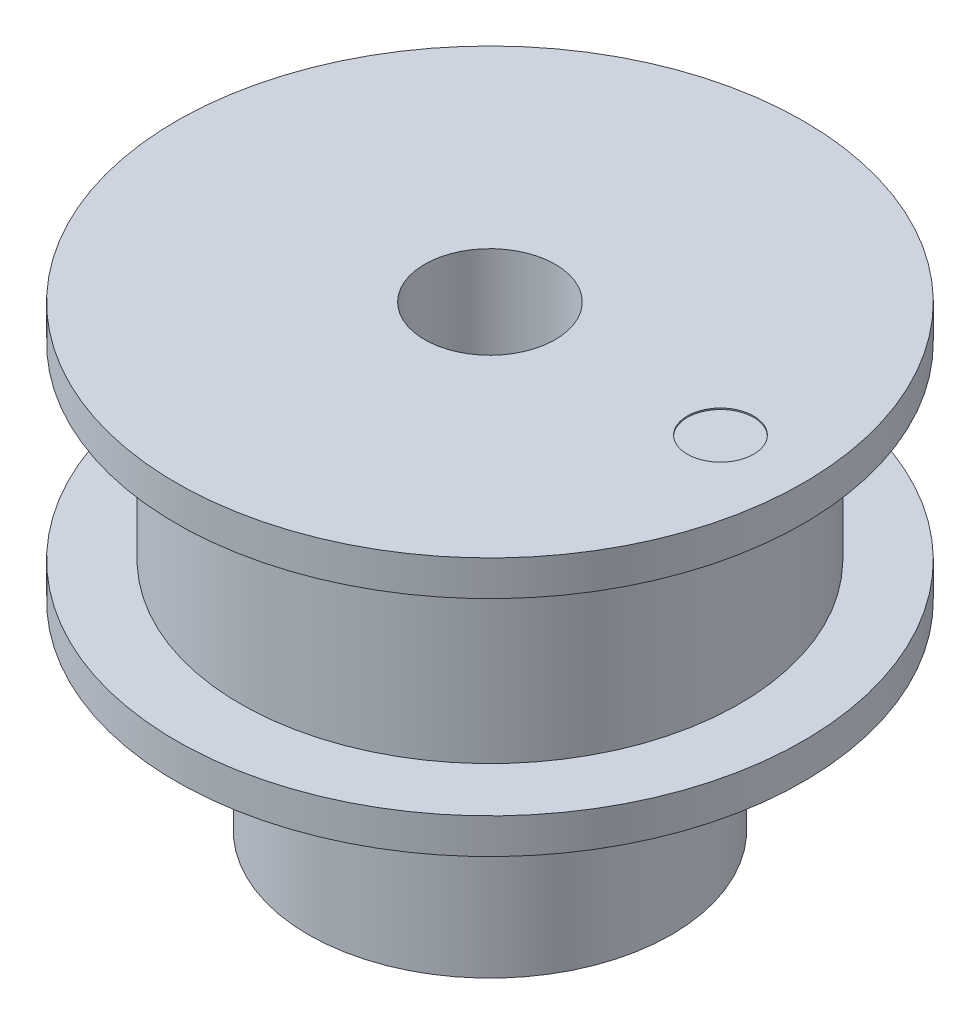
SolidWorks part; units mm, degrees
ref_plane "Front Plane" through (0, 0, 0) normal (0, 0, 1) x (1, 0, 0)
ref_plane "Top Plane" through (0, 0, 0) normal (0, 1, 0) x (1, 0, 0)
ref_plane "Right Plane" through (0, 0, 0) normal (1, 0, 0) x (0, 0, -1)
sketch "Sketch1" plane through (0, 0, 0) normal (0, 0, 1) x (1, 0, 0)
  line L0 (0, 0) -> (0, 17.5) construction
  line L1 (0, 0) -> (2.5, 0) construction
  line L2 (2.5, 0) -> (2.5, 17.5)
  line L3 (2.5, 17.5) -> (0, 17.5) construction
  line L4 (2.5, 0) -> (6.95, 0)
  line L5 (6.95, 0) -> (6.95, 7.6)
  line L6 (6.95, 7.6) -> (12, 7.6)
  line L7 (12, 7.6) -> (12, 8.95)
  line L8 (12, 8.95) -> (9.55, 8.95)
  line L9 (9.55, 8.95) -> (9.55, 16.15)
  line L10 (9.55, 16.15) -> (12, 16.15)
  line L11 (12, 16.15) -> (12, 17.5)
  line L12 (12, 17.5) -> (2.5, 17.5)
  dimension "D1" = 17.5
  dimension "D2" = 2.5
  dimension "D3" = 6.95
  dimension "D4" = 9.9
  dimension "D5" = 7.2
  dimension "D6" = 12
  dimension "D7" = 9.55
revolve "Revolve1" add sketch "Sketch1" angle 360 about L0
sketch "Sketch2" plane through (0, 17.5, 0) normal (0, 1, 0) x (1, 0, 0)
  line L0 (0, 0) -> (8.825, 0) construction
  line L1 (8.825, 0) -> (12, 0) construction
  circle A0 centre (0, 0) radius 12 construction
  circle A1 centre (8.825, 0) radius 1.27
  dimension "D1" = 2.54
  dimension "D2" = 3.175
extrude "Cut-Extrude1" cut sketch "Sketch2" against normal blind 0.0508
